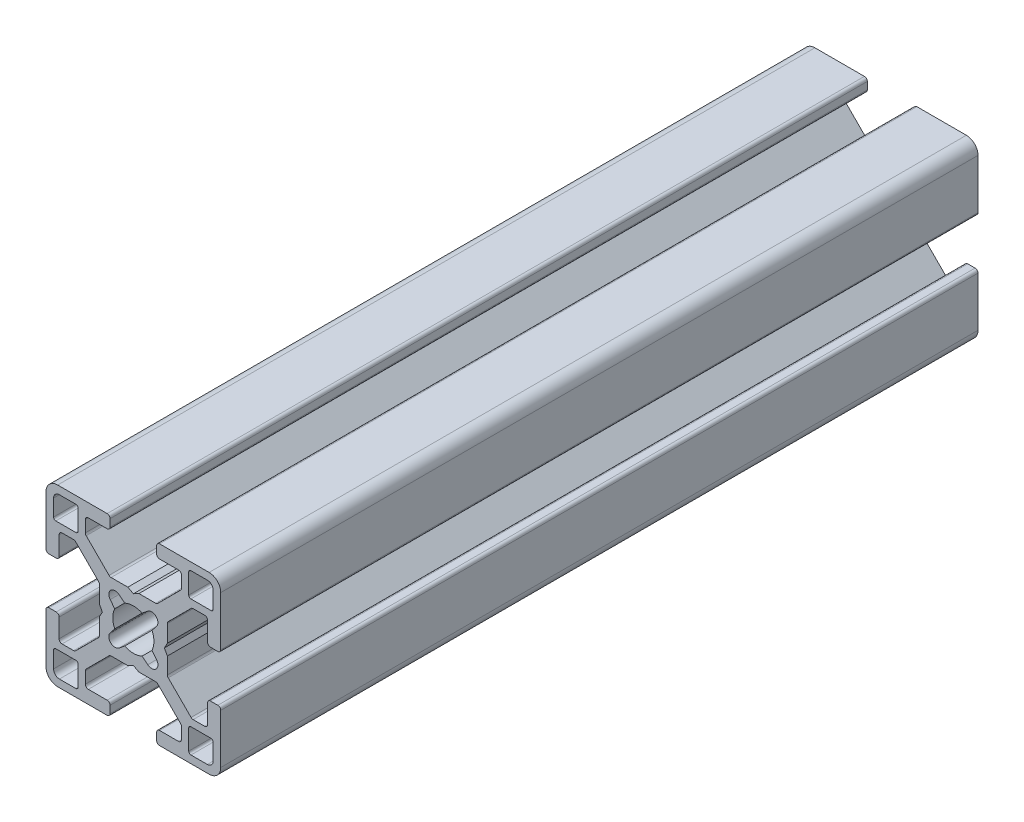
SolidWorks part; units mm, degrees
material "6105-T5 Aluminum"
ref_plane "Front Plane" through (0, 0, 0) normal (0, 0, 1) x (1, 0, 0)
ref_plane "Top Plane" through (0, 0, 0) normal (0, 1, 0) x (1, 0, 0)
ref_plane "Right Plane" through (0, 0, 0) normal (1, 0, 0) x (0, 0, -1)
sketch "Sketch1" plane through (0, 0, 0) normal (0, 0, 1) x (1, 0, 0)
  line L0 (9.5, -13.3189) -> (9.5, -9.88)
  line L1 (9.88, -9.5) -> (13.3189, -9.5)
  line L2 (13.6999, -9.881) -> (13.6999, -12.6999)
  line L3 (12.6999, -13.6999) -> (9.881, -13.6999)
  line L4 (-13.3189, -9.5) -> (-9.88, -9.5)
  line L5 (-9.5, -9.88) -> (-9.5, -13.3189)
  line L6 (-9.881, -13.6999) -> (-12.6999, -13.6999)
  line L7 (-13.6999, -12.6999) -> (-13.6999, -9.881)
  line L8 (-1.4942, -3.1981) -> (-2.4733, -3.9799)
  line L9 (-3.9799, -2.4733) -> (-3.1981, -1.4942)
  line L10 (-3.1981, 1.4942) -> (-3.9799, 2.4733)
  line L11 (-2.4733, 3.9799) -> (-1.4942, 3.1981)
  line L12 (1.4942, 3.1981) -> (2.4733, 3.9799)
  line L13 (3.9799, 2.4733) -> (3.1981, 1.4942)
  line L14 (3.1981, -1.4942) -> (3.9799, -2.4733)
  line L15 (2.4733, -3.9799) -> (1.4942, -3.1981)
  line L16 (-9.5, 13.3189) -> (-9.5, 9.88)
  line L17 (-9.88, 9.5) -> (-13.3189, 9.5)
  line L18 (-13.6999, 9.881) -> (-13.6999, 12.6999)
  line L19 (-12.6999, 13.6999) -> (-9.881, 13.6999)
  line L20 (9.881, 13.6999) -> (12.6999, 13.6999)
  line L21 (13.6999, 12.6999) -> (13.6999, 9.881)
  line L22 (13.3189, 9.5) -> (9.88, 9.5)
  line L23 (9.5, 9.88) -> (9.5, 13.3189)
  line L24 (12.7425, -4.5) -> (12.7425, -7.7325)
  line L25 (12.2428, -8.25) -> (10.2602, -8.25)
  line L26 (9.9066, -8.1035) -> (5.9811, -4.178)
  line L27 (5.8347, -3.8245) -> (5.8347, -1.0125)
  line L28 (5.8347, -1.0125) -> (5.3247, -0.0625)
  line L29 (5.3247, -0.0625) -> (5.8347, 0.8875)
  line L30 (5.8347, 0.8875) -> (5.8347, 3.8245)
  line L31 (5.9811, 4.178) -> (9.9066, 8.1035)
  line L32 (10.2602, 8.25) -> (12.2428, 8.25)
  line L33 (12.7425, 7.7325) -> (12.7425, 4.5)
  line L34 (13.2425, 4) -> (14.4999, 4)
  line L35 (14.9999, 4.5) -> (14.9999, 12.9999)
  line L36 (12.9999, 14.9999) -> (4.5, 14.9999)
  line L37 (4, 14.4999) -> (4, 13.2425)
  line L38 (4.5, 12.7425) -> (7.7325, 12.7425)
  line L39 (8.25, 12.2428) -> (8.25, 10.2602)
  line L40 (8.1035, 9.9066) -> (4.178, 5.9811)
  line L41 (3.8245, 5.8347) -> (0.95, 5.8347)
  line L42 (0.95, 5.8347) -> (0, 5.3247)
  line L43 (0, 5.3247) -> (-0.95, 5.8347)
  line L44 (-0.95, 5.8347) -> (-3.8245, 5.8347)
  line L45 (-4.178, 5.9811) -> (-8.1035, 9.9066)
  line L46 (-8.25, 10.2602) -> (-8.25, 12.2428)
  line L47 (-7.7325, 12.7425) -> (-4.5, 12.7425)
  line L48 (-4, 13.2425) -> (-4, 14.4999)
  line L49 (-4.5, 14.9999) -> (-12.9999, 14.9999)
  line L50 (-14.9999, 12.9999) -> (-14.9999, 4.5)
  line L51 (-14.4999, 4) -> (-13.2425, 4)
  line L52 (-12.7425, 4.5) -> (-12.7425, 7.7325)
  line L53 (-12.2428, 8.25) -> (-10.2602, 8.25)
  line L54 (-9.9066, 8.1035) -> (-5.9811, 4.178)
  line L55 (-5.8347, 3.8245) -> (-5.8347, 0.8875)
  line L56 (-5.8347, 0.8875) -> (-5.3247, -0.0625)
  line L57 (-5.3247, -0.0625) -> (-5.8347, -1.0125)
  line L58 (-5.8347, -1.0125) -> (-5.8347, -3.8245)
  line L59 (-5.9811, -4.178) -> (-9.9066, -8.1035)
  line L60 (-10.2602, -8.25) -> (-12.2428, -8.25)
  line L61 (-12.7425, -7.7325) -> (-12.7425, -4.5)
  line L62 (-13.2425, -4) -> (-14.4999, -4)
  line L63 (-14.9999, -4.5) -> (-14.9999, -12.9999)
  line L64 (-12.9999, -14.9999) -> (-4.5, -14.9999)
  line L65 (-4, -14.4999) -> (-4, -13.2425)
  line L66 (-4.5, -12.7425) -> (-7.7325, -12.7425)
  line L67 (-8.25, -12.2428) -> (-8.25, -10.2602)
  line L68 (-8.1035, -9.9066) -> (-4.178, -5.9811)
  line L69 (-3.8245, -5.8347) -> (-0.95, -5.8347)
  line L70 (-0.95, -5.8347) -> (0, -5.3247)
  line L71 (0, -5.3247) -> (0.95, -5.8347)
  line L72 (0.95, -5.8347) -> (3.8245, -5.8347)
  line L73 (4.178, -5.9811) -> (8.1035, -9.9066)
  line L74 (8.25, -10.2602) -> (8.25, -12.2428)
  line L75 (7.7325, -12.7425) -> (4.5, -12.7425)
  line L76 (4, -13.2425) -> (4, -14.4999)
  line L77 (4.5, -14.9999) -> (12.9999, -14.9999)
  line L78 (14.9999, -12.9999) -> (14.9999, -4.5)
  line L79 (14.4999, -4) -> (13.2425, -4)
  arc A0 (9.5, -13.3189) -> (9.881, -13.6999) centre (9.881, -13.3189) ccw
  arc A1 (9.88, -9.5) -> (9.5, -9.88) centre (9.88, -9.88) ccw
  arc A2 (13.6999, -9.881) -> (13.3189, -9.5) centre (13.3189, -9.881) ccw
  arc A3 (12.6999, -13.6999) -> (13.6999, -12.6999) centre (12.6999, -12.6999) ccw
  arc A4 (-13.3189, -9.5) -> (-13.6999, -9.881) centre (-13.3189, -9.881) ccw
  arc A5 (-9.5, -9.88) -> (-9.88, -9.5) centre (-9.88, -9.88) ccw
  arc A6 (-9.881, -13.6999) -> (-9.5, -13.3189) centre (-9.881, -13.3189) ccw
  arc A7 (-13.6999, -12.6999) -> (-12.6999, -13.6999) centre (-12.6999, -12.6999) ccw
  arc A8 (-1.4942, -3.1981) -> (1.4942, -3.1981) centre (0, 0) ccw
  arc A9 (-3.9799, -2.4733) -> (-2.4733, -3.9799) centre (-3.1422, -3.1422) ccw
  arc A10 (-3.1981, 1.4942) -> (-3.1981, -1.4942) centre (0, 0) ccw
  arc A11 (-2.4733, 3.9799) -> (-3.9799, 2.4733) centre (-3.1422, 3.1422) ccw
  arc A12 (1.4942, 3.1981) -> (-1.4942, 3.1981) centre (0, 0) ccw
  arc A13 (3.9799, 2.4733) -> (2.4733, 3.9799) centre (3.1422, 3.1422) ccw
  arc A14 (3.1981, -1.4942) -> (3.1981, 1.4942) centre (0, 0) ccw
  arc A15 (2.4733, -3.9799) -> (3.9799, -2.4733) centre (3.1422, -3.1422) ccw
  arc A16 (-9.5, 13.3189) -> (-9.881, 13.6999) centre (-9.881, 13.3189) ccw
  arc A17 (-9.88, 9.5) -> (-9.5, 9.88) centre (-9.88, 9.88) ccw
  arc A18 (-13.6999, 9.881) -> (-13.3189, 9.5) centre (-13.3189, 9.881) ccw
  arc A19 (-12.6999, 13.6999) -> (-13.6999, 12.6999) centre (-12.6999, 12.6999) ccw
  arc A20 (9.881, 13.6999) -> (9.5, 13.3189) centre (9.881, 13.3189) ccw
  arc A21 (13.6999, 12.6999) -> (12.6999, 13.6999) centre (12.6999, 12.6999) ccw
  arc A22 (13.3189, 9.5) -> (13.6999, 9.881) centre (13.3189, 9.881) ccw
  arc A23 (9.5, 9.88) -> (9.88, 9.5) centre (9.88, 9.88) ccw
  arc A24 (13.2425, -4) -> (12.7425, -4.5) centre (13.2425, -4.5) ccw
  arc A25 (12.2428, -8.25) -> (12.7425, -7.7325) centre (12.2428, -7.75) ccw
  arc A26 (9.9066, -8.1035) -> (10.2602, -8.25) centre (10.2602, -7.75) ccw
  arc A27 (5.8347, -3.8245) -> (5.9811, -4.178) centre (6.3347, -3.8245) ccw
  arc A28 (5.9811, 4.178) -> (5.8347, 3.8245) centre (6.3347, 3.8245) ccw
  arc A29 (10.2602, 8.25) -> (9.9066, 8.1035) centre (10.2602, 7.75) ccw
  arc A30 (12.7425, 7.7325) -> (12.2428, 8.25) centre (12.2428, 7.75) ccw
  arc A31 (12.7425, 4.5) -> (13.2425, 4) centre (13.2425, 4.5) ccw
  arc A32 (14.4999, 4) -> (14.9999, 4.5) centre (14.4999, 4.5) ccw
  arc A33 (14.9999, 12.9999) -> (12.9999, 14.9999) centre (12.9999, 12.9999) ccw
  arc A34 (4.5, 14.9999) -> (4, 14.4999) centre (4.5, 14.4999) ccw
  arc A35 (4, 13.2425) -> (4.5, 12.7425) centre (4.5, 13.2425) ccw
  arc A36 (8.25, 12.2428) -> (7.7325, 12.7425) centre (7.75, 12.2428) ccw
  arc A37 (8.1035, 9.9066) -> (8.25, 10.2602) centre (7.75, 10.2602) ccw
  arc A38 (3.8245, 5.8347) -> (4.178, 5.9811) centre (3.8245, 6.3347) ccw
  arc A39 (-4.178, 5.9811) -> (-3.8245, 5.8347) centre (-3.8245, 6.3347) ccw
  arc A40 (-8.25, 10.2602) -> (-8.1035, 9.9066) centre (-7.75, 10.2602) ccw
  arc A41 (-7.7325, 12.7425) -> (-8.25, 12.2428) centre (-7.75, 12.2428) ccw
  arc A42 (-4.5, 12.7425) -> (-4, 13.2425) centre (-4.5, 13.2425) ccw
  arc A43 (-4, 14.4999) -> (-4.5, 14.9999) centre (-4.5, 14.4999) ccw
  arc A44 (-12.9999, 14.9999) -> (-14.9999, 12.9999) centre (-12.9999, 12.9999) ccw
  arc A45 (-14.9999, 4.5) -> (-14.4999, 4) centre (-14.4999, 4.5) ccw
  arc A46 (-13.2425, 4) -> (-12.7425, 4.5) centre (-13.2425, 4.5) ccw
  arc A47 (-12.2428, 8.25) -> (-12.7425, 7.7325) centre (-12.2428, 7.75) ccw
  arc A48 (-9.9066, 8.1035) -> (-10.2602, 8.25) centre (-10.2602, 7.75) ccw
  arc A49 (-5.8347, 3.8245) -> (-5.9811, 4.178) centre (-6.3347, 3.8245) ccw
  arc A50 (-5.9811, -4.178) -> (-5.8347, -3.8245) centre (-6.3347, -3.8245) ccw
  arc A51 (-10.2602, -8.25) -> (-9.9066, -8.1035) centre (-10.2602, -7.75) ccw
  arc A52 (-12.7425, -7.7325) -> (-12.2428, -8.25) centre (-12.2428, -7.75) ccw
  arc A53 (-12.7425, -4.5) -> (-13.2425, -4) centre (-13.2425, -4.5) ccw
  arc A54 (-14.4999, -4) -> (-14.9999, -4.5) centre (-14.4999, -4.5) ccw
  arc A55 (-14.9999, -12.9999) -> (-12.9999, -14.9999) centre (-12.9999, -12.9999) ccw
  arc A56 (-4.5, -14.9999) -> (-4, -14.4999) centre (-4.5, -14.4999) ccw
  arc A57 (-4, -13.2425) -> (-4.5, -12.7425) centre (-4.5, -13.2425) ccw
  arc A58 (-8.25, -12.2428) -> (-7.7325, -12.7425) centre (-7.75, -12.2428) ccw
  arc A59 (-8.1035, -9.9066) -> (-8.25, -10.2602) centre (-7.75, -10.2602) ccw
  arc A60 (-3.8245, -5.8347) -> (-4.178, -5.9811) centre (-3.8245, -6.3347) ccw
  arc A61 (4.178, -5.9811) -> (3.8245, -5.8347) centre (3.8245, -6.3347) ccw
  arc A62 (8.25, -10.2602) -> (8.1035, -9.9066) centre (7.75, -10.2602) ccw
  arc A63 (7.7325, -12.7425) -> (8.25, -12.2428) centre (7.75, -12.2428) ccw
  arc A64 (4.5, -12.7425) -> (4, -13.2425) centre (4.5, -13.2425) ccw
  arc A65 (4, -14.4999) -> (4.5, -14.9999) centre (4.5, -14.4999) ccw
  arc A66 (12.9999, -14.9999) -> (14.9999, -12.9999) centre (12.9999, -12.9999) ccw
  arc A67 (14.9999, -4.5) -> (14.4999, -4) centre (14.4999, -4.5) ccw
extrude "Extrude1" add sketch "Sketch1" against normal blind 130
